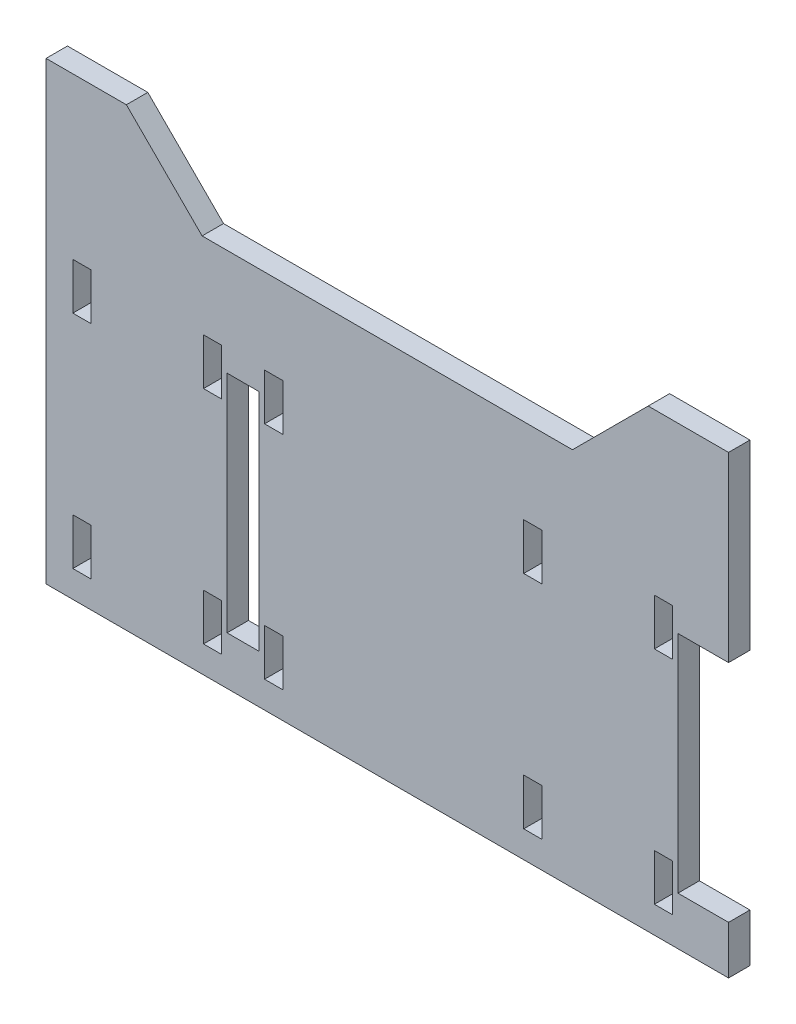
SolidWorks part; units mm, degrees
ref_plane "Front Plane" through (0, 0, 0) normal (0, 0, 1) x (1, 0, 0)
ref_plane "Top Plane" through (0, 0, 0) normal (0, 1, 0) x (1, 0, 0)
ref_plane "Right Plane" through (0, 0, 0) normal (1, 0, 0) x (0, 0, -1)
sketch "Sketch1" plane through (0, 0, 0) normal (0, 0, 1) x (1, 0, 0)
  line L0 (0, 66.0849) -> (0, -70.4198) construction
  line L6 (-37.3, 25) -> (-33.9, 25)
  line L7 (22.5, 25) -> (25.9, 25)
  line L8 (22.5, 25) -> (22.5, 16.3)
  line L9 (22.5, 16.3) -> (25.9, 16.3)
  line L10 (25.9, 25) -> (25.9, 16.3)
  line L11 (-103.5149, 0) -> (102.2922, 0) construction
  line L12 (22.5, -16.3) -> (25.9, -16.3)
  line L13 (22.5, -25) -> (22.5, -16.3)
  line L14 (25.9, -25) -> (25.9, -16.3)
  line L15 (22.5, -25) -> (25.9, -25)
  line L16 (-22.5, 25) -> (-25.9, 25)
  line L17 (-22.5, 25) -> (-22.5, 16.3)
  line L18 (-25.9, 25) -> (-25.9, 16.3)
  line L19 (-22.5, 16.3) -> (-25.9, 16.3)
  line L20 (-22.5, -16.3) -> (-25.9, -16.3)
  line L21 (-22.5, -25) -> (-22.5, -16.3)
  line L22 (-25.9, -25) -> (-25.9, -16.3)
  line L23 (-22.5, -25) -> (-25.9, -25)
  line L39 (46.9, 25) -> (50.3, 25)
  line L40 (46.9, 25) -> (46.9, 16.3)
  line L41 (46.9, 16.3) -> (50.3, 16.3)
  line L42 (50.3, 25) -> (50.3, 16.3)
  line L43 (46.9, -16.3) -> (50.3, -16.3)
  line L44 (46.9, -16.3) -> (46.9, -25)
  line L45 (46.9, -25) -> (50.3, -25)
  line L46 (50.3, -16.3) -> (50.3, -25)
  line L47 (-37.3, 25) -> (-37.3, 16.3)
  line L48 (-37.3, 16.3) -> (-33.9, 16.3)
  line L49 (-33.9, 25) -> (-33.9, 16.3)
  line L50 (-37.3, -16.3) -> (-33.9, -16.3)
  line L51 (-37.3, -16.3) -> (-37.3, -25)
  line L52 (-37.3, -25) -> (-33.9, -25)
  line L53 (-33.9, -16.3) -> (-33.9, -25)
  line L57 (-66.7, 30) -> (-66.7, -30)
  line L59 (-66.7, 30) -> (55.3, 30)
  line L60 (-61.7, 25) -> (-58.3, 25)
  line L61 (-61.7, 25) -> (-61.7, 16.3)
  line L62 (-61.7, 16.3) -> (-58.3, 16.3)
  line L63 (-58.3, 25) -> (-58.3, 16.3)
  line L64 (-61.7, -16.3) -> (-58.3, -16.3)
  line L65 (-61.7, -16.3) -> (-61.7, -25)
  line L66 (-61.7, -25) -> (-58.3, -25)
  line L67 (-58.3, -16.3) -> (-58.3, -25)
  line L68 (-66.7, -30) -> (55.3, -30)
  line L69 (55.3, 30) -> (60.7402, 30)
  line L70 (60.7402, 30) -> (60.7402, -30) construction
  line L71 (60.7402, -30) -> (55.3, -30)
  line L72 (51.3, 21) -> (58.8, 21)
  line L73 (58.8, 21) -> (58.8, -21) construction
  line L74 (58.8, -21) -> (51.3, -21)
  line L75 (51.3, -21) -> (51.3, 21)
  line L76 (-26.9, 21) -> (-32.9, 21)
  line L77 (-32.9, 21) -> (-32.9, -21)
  line L78 (-32.9, -21) -> (-26.9, -21)
  line L79 (-26.9, -21) -> (-26.9, 21)
  line L80 (58.8, 21) -> (60.7402, 21)
  line L81 (58.8, -21) -> (60.7402, -21)
  line L82 (60.7402, 21) -> (60.7402, 30)
  line L83 (60.7402, -21) -> (60.7402, -30)
  point P0 (0, 0)
  point P56 (50.3, 20.65)
  dimension "D2" = 60
  dimension "D3" = 8
  dimension "D4" = 1
  dimension "D5" = 3.4
  dimension "D6" = 8.7
  dimension "D7" = 45
  dimension "D8" = 21
  dimension "D9" = 21
  dimension "D10" = 5
  dimension "D11" = 5
  dimension "D12" = 7.5
  dimension "D13" = 9
  dimension "D14" = 9
  dimension "D15" = 1
  dimension "D16" = 1
  dimension "D17" = 9
  dimension "D18" = 9
extrude "Boss-Extrude1" add sketch "Sketch1" along normal blind 4
sketch "Sketch2" plane through (0, 0, 0) normal (0, 0, 1) x (1, 0, 0)
  line L0 (-66.7, 30) -> (-66.7, 55)
  line L1 (-66.7, 55) -> (-51.7, 55)
  line L2 (-51.7, 55) -> (-37.5579, 40.8579)
  line L7 (60.7402, 30) -> (-66.7, 30)
  line L8 (45.7402, 55) -> (60.7402, 55)
  line L9 (60.7402, 55) -> (60.7402, 30)
  line L10 (45.7402, 55) -> (31.5981, 40.8579)
  line L11 (31.5981, 40.8579) -> (-37.5579, 40.8579)
  line L13 (60.7402, 21) -> (60.7402, 30) construction
  dimension "D1" = 25
  dimension "D2" = 15
  dimension "D3" = 135
  dimension "D4" = 20
extrude "Boss-Extrude2" add sketch "Sketch2" along normal blind 4
